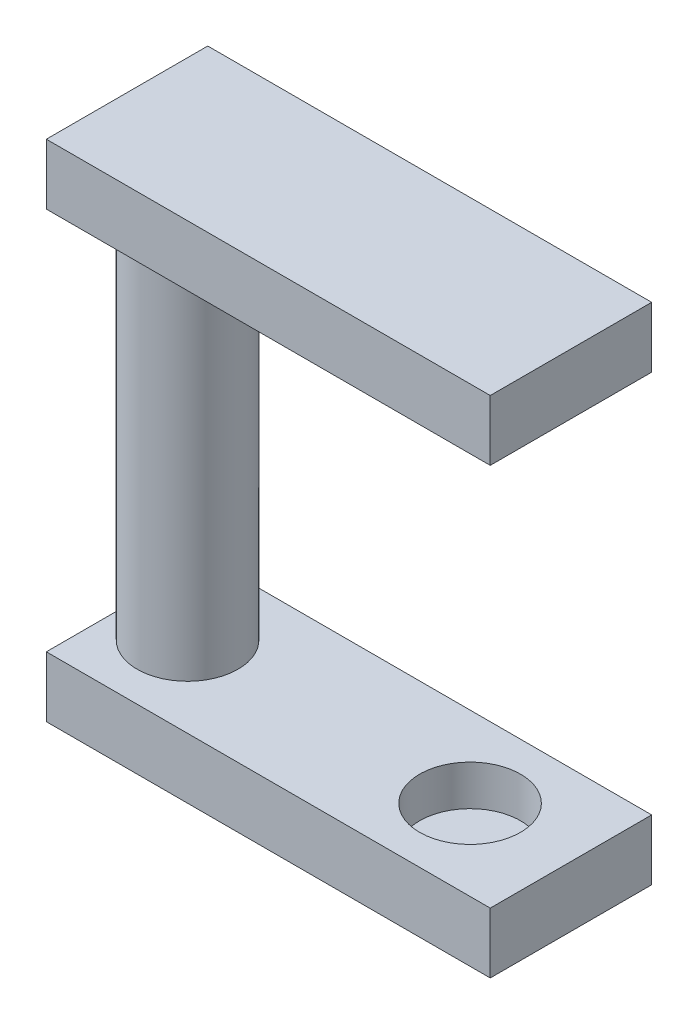
SolidWorks part; units mm, degrees
ref_plane "Front Plane" through (0, 0, 0) normal (0, 0, 1) x (1, 0, 0)
ref_plane "Top Plane" through (0, 0, 0) normal (0, 1, 0) x (1, 0, 0)
ref_plane "Right Plane" through (0, 0, 0) normal (1, 0, 0) x (0, 0, -1)
sketch "Sketch1" plane through (0, 0, 0) normal (0, 1, 0) x (1, 0, 0)
  circle A0 centre (0, 0) radius 6.35
  dimension "D1" = 12.7
extrude "Boss-Extrude1" add sketch "Sketch1" along normal blind 48.26
sketch "Sketch2" plane through (0, 48.26, 0) normal (0, 1, 0) x (1, 0, 0)
  line L1 (-7.62, 10.16) -> (48.26, 10.16)
  line L2 (-7.62, 10.16) -> (-7.62, -10.16)
  line L3 (-7.62, -10.16) -> (48.26, -10.16)
  line L4 (48.26, 10.16) -> (48.26, -10.16)
  line L5 (20.32, -10.16) -> (20.32, 10.16) construction
  line L6 (-7.62, 0) -> (48.26, 0) construction
  circle A0 centre (0, 0) radius 6.35 construction
  point P836 (20.32, 0)
  dimension "D1" = 10.16
  dimension "D2" = 20.32
  dimension "D3" = 55.88
  dimension "D4" = 7.62
extrude "Boss-Extrude2" add sketch "Sketch2" along normal blind 7.62
sketch "Sketch3" plane through (0, 0, 0) normal (0, -1, 0) x (1, 0, 0)
  line L0 (-7.62, 10.16) -> (48.26, 10.16)
  line L1 (-7.62, 10.16) -> (-7.62, -10.16)
  line L2 (-7.62, -10.16) -> (48.26, -10.16)
  line L4 (20.32, -10.16) -> (20.32, 10.16) construction
  line L5 (-7.62, 0) -> (55.88, 0) construction
  line L6 (48.26, 10.16) -> (48.26, -10.16)
  point P8 (20.32, 0)
  dimension "D1" = 20.32
  dimension "D2" = 55.88
extrude "Boss-Extrude3" add sketch "Sketch3" along normal blind 7.62
sketch "Sketch5" plane through (0, 0, 0) normal (0, 1, 0) x (1, 0, 0)
  line L1 (-7.62, 10.16) -> (48.26, 10.16) construction
  line L2 (48.26, -10.16) -> (48.26, 10.16) construction
  circle A0 centre (35.56, 0) radius 6.35
  point P6 (41.91, 0)
  dimension "D1" = 12.7
  dimension "D2" = 12.7
  dimension "D3" = 10.16
extrude "Cut-Extrude1" cut sketch "Sketch5" against normal blind 5.08
sketch "Sketch6" plane through (0, 48.26, 0) normal (0, -1, 0) x (1, 0, 0)
  line L0 (48.26, -10.16) -> (48.26, 10.16) construction
  line L1 (48.26, 10.16) -> (-7.62, 10.16) construction
  circle A0 centre (35.56, 0) radius 6.35
  dimension "D2" = 12.7
  dimension "D1" = 12.7
  dimension "D3" = 10.16
extrude "Cut-Extrude2" cut sketch "Sketch6" against normal blind 5.08
